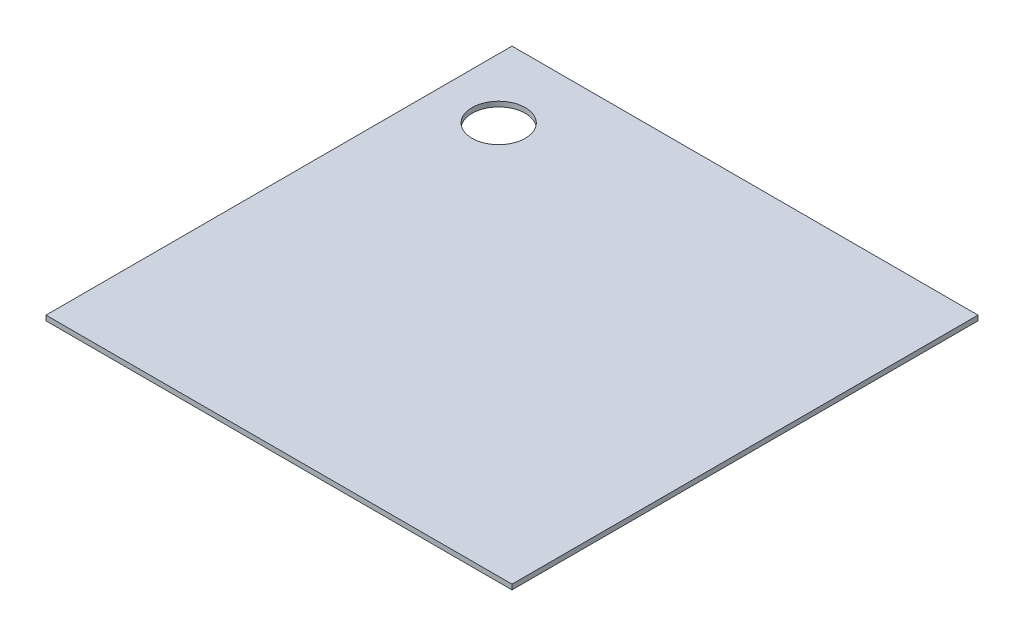
SolidWorks part; units mm, degrees
ref_plane "Front Plane" through (0, 0, 0) normal (0, 0, 1) x (1, 0, 0)
ref_plane "Top Plane" through (0, 0, 0) normal (0, 1, 0) x (1, 0, 0)
ref_plane "Right Plane" through (0, 0, 0) normal (1, 0, 0) x (0, 0, -1)
sketch "Sketch1" plane through (0, 0, 0) normal (0, 1, 0) x (1, 0, 0)
  line L1 (140, -140) -> (-140, -140)
  line L2 (140, -140) -> (140, 140)
  line L3 (140, 140) -> (-140, 140)
  line L4 (-140, -140) -> (-140, 140)
  line L5 (140, -140) -> (-140, 140) construction
  line L6 (140, 140) -> (-140, -140) construction
  circle A0 centre (-104, 96) radius 12.5 construction
  circle A2 centre (-104, 96) radius 16
  point P0 (0, 0)
  dimension "D2" = 25
  dimension "D4" = 36
  dimension "D5" = 44
  dimension "D3" = 32
  dimension "D1" = 280
extrude "Boss-Extrude1" add sketch "Sketch1" along normal mid plane 3
